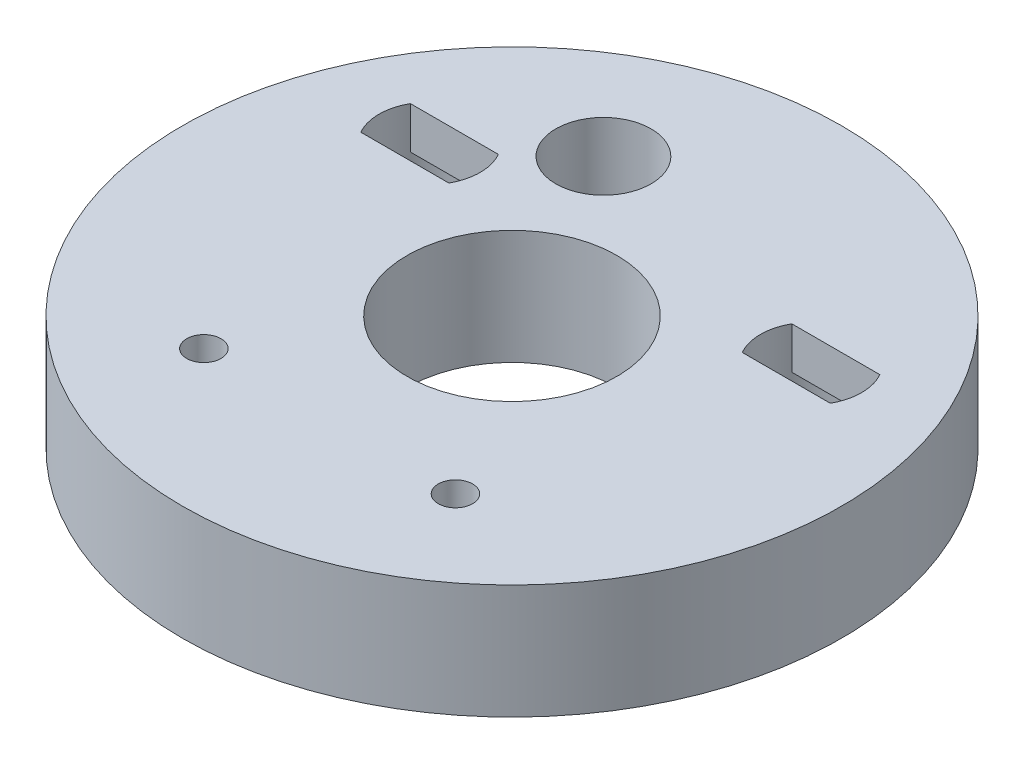
SolidWorks part; units mm, degrees
ref_plane "前视基准面" through (0, 0, 0) normal (0, 0, 1) x (1, 0, 0)
ref_plane "上视基准面" through (0, 0, 0) normal (0, 1, 0) x (1, 0, 0)
ref_plane "右视基准面" through (0, 0, 0) normal (1, 0, 0) x (0, 0, -1)
sketch "草图1" plane through (0, 0, 0) normal (0, 1, 0) x (1, 0, 0)
  line L0 (10, 5.6789) -> (-10, 5.6789) construction
  line L1 (0, 0) -> (0, 21.4139) construction
  line L2 (-6.595, -9.5611) -> (6.595, -9.5611) construction
  line L3 (-0.6445, -0.366) -> (22.2352, 12.6272) construction
  circle A0 centre (0, 0) radius 17.28
  circle A1 centre (0, 0) radius 5 construction
  circle A2 centre (0, 0) radius 5.5
  circle A3 centre (10, 5.6789) radius 2.5 construction
  circle A4 centre (-10, 5.6789) radius 2.5 construction
  circle A5 centre (6.595, -9.5611) radius 1.76 construction
  circle A6 centre (-6.595, -9.5611) radius 1.76 construction
  circle A7 centre (-10, 5.6789) radius 2.65
  circle A8 centre (-6.595, -9.5611) radius 1.9
  circle A9 centre (6.595, -9.5611) radius 1.9
  circle A10 centre (10, 5.6789) radius 2.65
  point P14 (0, 5.6789)
  point P21 (0, -9.5611)
  dimension "D1" = 34.56
  dimension "D2" = 10
  dimension "D3" = 11
  dimension "D5" = 11.5
  dimension "D7" = 5
  dimension "D8" = 13.19
  dimension "D4" = 20
  dimension "D6" = 3.52
  dimension "D10" = 5.3
  dimension "D11" = 3.8
  dimension "D9" = 15.24
extrude "凸台-拉伸1" add sketch "草图1" along normal blind 3.8
sketch "草图2" plane through (0, 3.8, 0) normal (0, 1, 0) x (1, 0, 0)
  line L0 (-7.35, 18.1851) -> (-7.35, -3.106) construction
  circle A1 centre (0, 0) radius 17.28
  circle A2 centre (0, 0) radius 17.28 construction
  circle A3 centre (-10, 5.6789) radius 2.5 construction
  circle A4 centre (-4.85, 9.6447) radius 2.5
  circle A6 centre (-10, 5.6789) radius 2.65 construction
  dimension "D2" = 6.5
  dimension "D3" = 5
  dimension "D1" = 0
extrude "切除-拉伸1" cut sketch "草图2" against normal through all
sketch "草图3" plane through (0, 3.8, 0) normal (0, 1, 0) x (1, 0, 0)
  line L0 (-12.3092, 4.3789) -> (-7.6908, 4.3789)
  line L1 (-12.3092, 6.9789) -> (-7.6908, 6.9789)
  line L2 (-10, 6.9789) -> (-10, 4.3789) construction
  line L3 (0, 0) -> (0, 3.4524) construction
  line L4 (12.3092, 4.3789) -> (7.6908, 4.3789)
  line L5 (12.3092, 6.9789) -> (7.6908, 6.9789)
  circle A0 centre (6.595, -9.5611) radius 1.9 construction
  circle A1 centre (0, 0) radius 17.28
  circle A2 centre (0, 0) radius 17.28
  circle A3 centre (-6.595, -9.5611) radius 1.9 construction
  circle A5 centre (-10, 5.6789) radius 2.65 construction
  circle A6 centre (0, 0) radius 5.5 construction
  circle A7 centre (-4.85, 9.6447) radius 2.5 construction
  circle A8 centre (6.595, -9.5611) radius 1.9 construction
  circle A9 centre (-6.595, -9.5611) radius 1.9 construction
  arc A11 (-12.3092, 6.9789) -> (-12.3092, 4.3789) centre (-10, 5.6789) ccw
  circle A12 centre (0, 0) radius 5.5
  circle A13 centre (-4.85, 9.6447) radius 2.5
  arc A14 (-7.6908, 4.3789) -> (-7.6908, 6.9789) centre (-10, 5.6789) ccw
  arc A15 (7.6908, 4.3789) -> (7.6908, 6.9789) centre (10, 5.6789) cw
  arc A16 (12.3092, 6.9789) -> (12.3092, 4.3789) centre (10, 5.6789) cw
  circle A17 centre (-6.595, -9.5611) radius 0.9
  circle A18 centre (6.595, -9.5611) radius 0.9
  dimension "D3" = 1.8
  dimension "D2" = 2.6
  dimension "D1" = 0
extrude "凸台-拉伸2" add sketch "草图3" along normal blind 2.2
